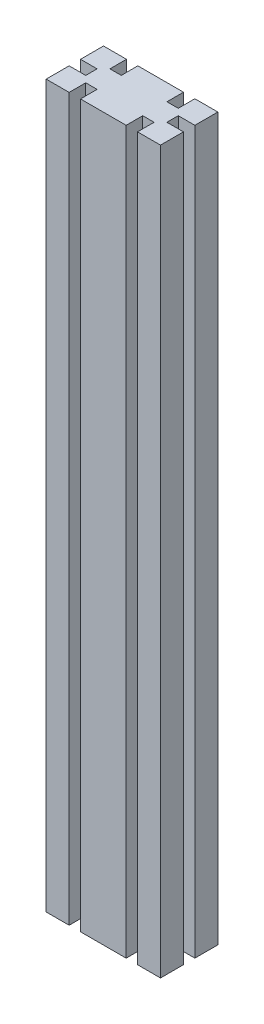
SolidWorks part; units mm, degrees
ref_plane "Front Plane" through (0, 0, 0) normal (0, 0, 1) x (1, 0, 0)
ref_plane "Top Plane" through (0, 0, 0) normal (0, 1, 0) x (1, 0, 0)
ref_plane "Right Plane" through (0, 0, 0) normal (1, 0, 0) x (0, 0, -1)
sketch "Sketch1" plane through (0, 0, 0) normal (0, 1, 0) x (1, 0, 0)
  line L0 (0, 0) -> (-40.259, 0) construction
  line L1 (-40.259, 20.193) -> (40.259, 20.193)
  line L2 (-40.259, 20.193) -> (-40.259, -20.193)
  line L3 (-40.259, -20.193) -> (40.259, -20.193)
  line L4 (40.259, 20.193) -> (40.259, -20.193)
  line L5 (-40.259, 20.193) -> (40.259, -20.193) construction
  line L6 (-40.259, -20.193) -> (40.259, 20.193) construction
  line L7 (0, 0) -> (0, -20.193) construction
  line L8 (24.075, -20.193) -> (24.075, -8.509)
  line L9 (-16.075, -20.193) -> (-24.075, -20.193)
  line L10 (-16.075, -20.193) -> (-16.075, -8.509)
  line L11 (-16.075, -8.509) -> (-24.075, -8.509)
  line L12 (-24.075, -20.193) -> (-24.075, -8.509)
  line L13 (16.075, -8.509) -> (24.075, -8.509)
  line L14 (16.075, -20.193) -> (16.075, -8.509)
  line L15 (16.075, -20.193) -> (24.075, -20.193)
  line L16 (16.075, 20.193) -> (24.075, 20.193)
  line L17 (16.075, 20.193) -> (16.075, 8.509)
  line L18 (16.075, 8.509) -> (24.075, 8.509)
  line L19 (-24.075, 20.193) -> (-24.075, 8.509)
  line L20 (-16.075, 8.509) -> (-24.075, 8.509)
  line L21 (-16.075, 20.193) -> (-16.075, 8.509)
  line L22 (-16.075, 20.193) -> (-24.075, 20.193)
  line L23 (24.075, 20.193) -> (24.075, 8.509)
  line L24 (28.575, -4) -> (40.259, -4)
  line L25 (-28.575, -4) -> (-40.259, -4)
  line L26 (-28.575, -4) -> (-28.575, 4)
  line L27 (-28.575, 4) -> (-40.259, 4)
  line L28 (-40.259, -4) -> (-40.259, 4)
  line L29 (-28.575, -4) -> (-40.259, 4) construction
  line L30 (-28.575, 4) -> (-40.259, -4) construction
  line L31 (28.575, -4) -> (28.575, 4)
  line L32 (28.575, 4) -> (40.259, 4)
  point P0 (0, 0)
  point P25 (-34.417, 0)
  dimension "D1" = 40.386
  dimension "D2" = 80.518
  dimension "D3" = 32.15
  dimension "D4" = 8
  dimension "D5" = 11.684
extrude "Boss-Extrude1" add sketch "Sketch1" along normal blind 508 contours L1 L23 L18 L17 L21 L20 L19 L2 L3 L12 L11 L10 L14 L13 L8 L4
